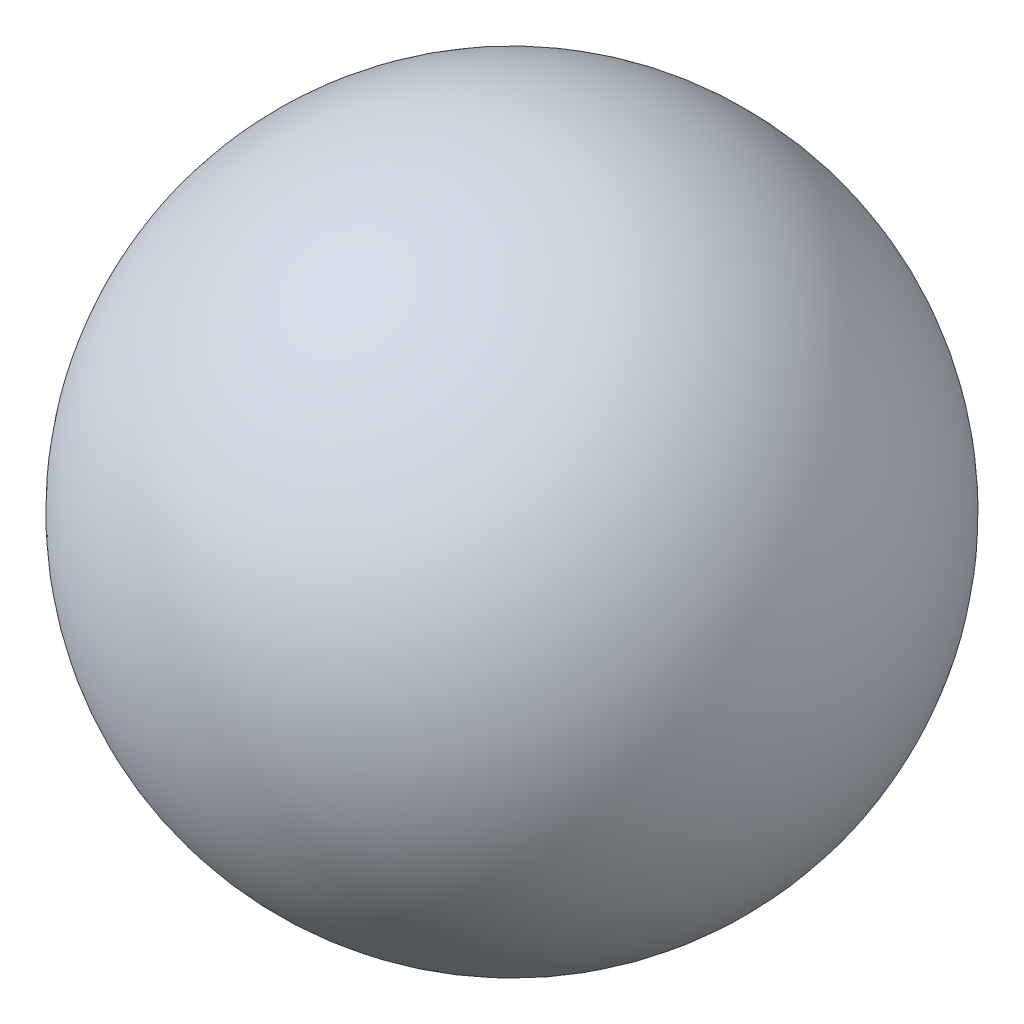
SolidWorks part; units mm, degrees
ref_plane "Piano frontale" through (0, 0, 0) normal (0, 0, 1) x (1, 0, 0)
ref_plane "Piano superiore" through (0, 0, 0) normal (0, 1, 0) x (1, 0, 0)
ref_plane "Piano destro" through (0, 0, 0) normal (1, 0, 0) x (0, 0, -1)
ref_plane "Piano1" through (0, 0, 0) normal (0, 0, 1) x (1, 0, 0)
sketch "Schizzo1" plane through (0, 0, 0) normal (0, 0, 1) x (1, 0, 0)
  line L0 (53.606, 66.275) -> (29.794, 66.275)
  line L1 (53.606, 66.275) -> (29.794, 66.275) construction
  arc A0 (29.794, 66.275) -> (53.606, 66.275) centre (41.7, 66.275) cw
revolve "Rivoluzione1" add sketch "Schizzo1" angle 360 about L1
